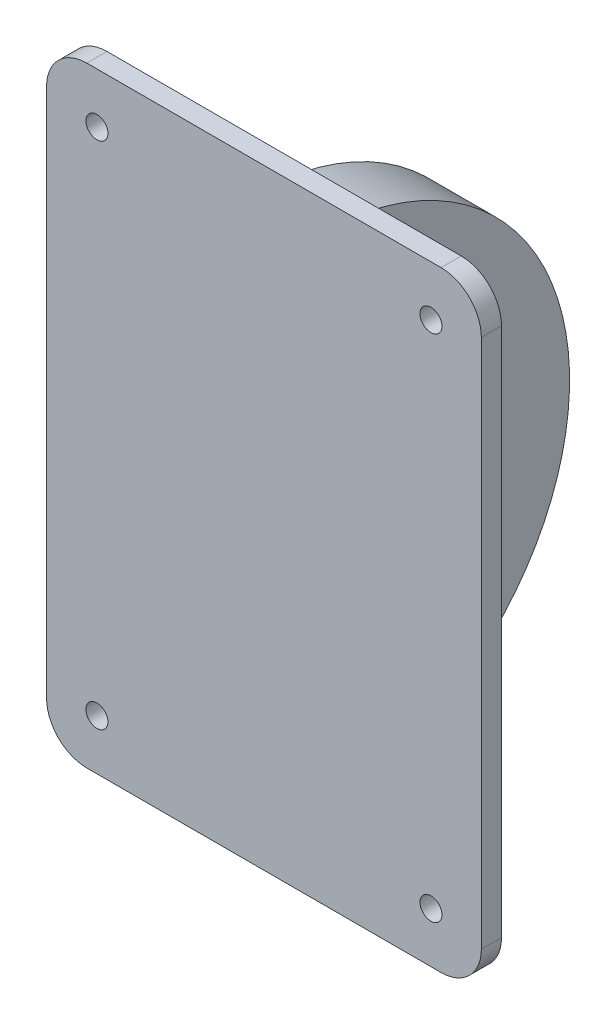
SolidWorks part; units mm, degrees
material "PE High Density"
ref_plane "Front Plane" through (0, 0, 0) normal (0, 0, 1) x (1, 0, 0)
ref_plane "Top Plane" through (0, 0, 0) normal (0, 1, 0) x (1, 0, 0)
ref_plane "Right Plane" through (0, 0, 0) normal (1, 0, 0) x (0, 0, -1)
sketch "Sketch1" plane through (0, 0, 0) normal (0, 0, 1) x (1, 0, 0)
  line L1 (-21.5755, 30.2941) -> (21.5754, 30.2941)
  line L2 (-21.5755, 30.2941) -> (-21.5754, -30.2941)
  line L3 (-21.5754, -30.2941) -> (21.5755, -30.2941)
  line L4 (21.5754, 30.2941) -> (21.5755, -30.2941)
  line L5 (-21.5755, 30.2941) -> (21.5755, -30.2941) construction
  line L6 (-21.5754, -30.2941) -> (21.5754, 30.2941) construction
  point P0 (0, 0)
  dimension "D1" = 60.5882
  dimension "D2" = 43.1509
extrude "Boss-Extrude1" add sketch "Sketch1" along normal blind 2
fillet "Fillet1" radius 4 4 edges at (-21.5754, -30.2941, 1) (21.5755, -30.2941, 1) (-21.5755, 30.2941, 1) (21.5754, 30.2941, 1)
sketch "Sketch2" plane through (0, 0, 2) normal (0, 0, 1) x (1, 0, 0)
  line L0 (17.5755, 30.2941) -> (-17.5755, 30.2941) construction
  line L1 (-21.5755, 26.2941) -> (-21.5755, -26.2941) construction
  line L2 (21.5755, -26.2941) -> (21.5755, 26.2941) construction
  line L3 (-17.5754, -30.2941) -> (17.5755, -30.2941) construction
  circle A0 centre (-16.5755, 25.2941) radius 1.0922
  circle A1 centre (16.5755, 25.2941) radius 1.0922
  circle A2 centre (-16.5755, -25.2941) radius 1.0922
  circle A3 centre (16.5755, -25.2941) radius 1.0922
  dimension "D1" = 2.1844
  dimension "D2" = 2.1844
  dimension "D3" = 2.1844
  dimension "D4" = 2.1844
  dimension "D5" = 5
  dimension "D6" = 5
  dimension "D7" = 5
  dimension "D8" = 5
  dimension "D9" = 5
  dimension "D10" = 5
  dimension "D11" = 5
  dimension "D12" = 5
extrude "Cut-Extrude1" cut sketch "Sketch2" against normal blind 2
cosmetic thread "Cosmetic Thread1" parameters "D2"=3.1844
cosmetic thread "Cosmetic Thread2" parameters "D2"=3.1844
cosmetic thread "Cosmetic Thread3" parameters "D2"=3.1844
cosmetic thread "Cosmetic Thread4" parameters "D2"=3.1844
sketch "Sketch5" plane through (0, 0, 0) normal (1, 0, 0) x (0, 0, -1)
  line L0 (0, 25) -> (0, -25) construction
  line L1 (0, 25) -> (0, -25)
  arc A0 (0, -25) -> (0, 25) centre (0, 0) ccw
  dimension "D1" = 50
extrude "Boss-Extrude2" add sketch "Sketch5" along normal mid plane 6.6667
sketch "Sketch6" plane through (3.3333, 0, 0) normal (1, 0, 0) x (0, 0, -1)
  line L0 (0, -26.2941) -> (0, 26.2941) construction
  line L1 (0, -30.2941) -> (-2, -30.2941) construction
  circle A0 centre (10.61, 0) radius 3
  dimension "D2" = 6
  dimension "D1" = 10.61
  dimension "D3" = 30.2941
extrude "Cut-Extrude2" cut sketch "Sketch6" against normal up to next
equation "\"userHeight\" = 2000mm'Users height"
equation "\"fin_hole_radius\"= 8 * 1500 / \"userHeight\"'Fin hole radius"
equation "\"fin_thickness\"= 5 * \"userHeight\" / 1500'Fin thickness"
equation "\"D1\" = \"fin_thickness\""
equation "\"D2@Sketch6\"=\"fin_hole_radius\""
equation "\"D1@Boss-Extrude2\"=\"fin_thickness\""
equation "\"fin_platform_width\"= IIF ( \"userHeight\" > 1850 , 43.1509 , 33.26 )'Platform width of fin part"
equation "\"D2@Sketch1\"=\"fin_platform_width\""
equation "\"fin_platform_height\"= IIF ( \"userHeight\" > 1850 , 60.58823 , 50 )'Platform height fin part"
equation "\"D1@Sketch1\"=\"fin_platform_height\""
equation "\"hole_position_y\"= 25 * \"fin_platform_height\" / 50'Fin platform position y"
equation "\"D3@Sketch6\"=\"hole_position_y\""
